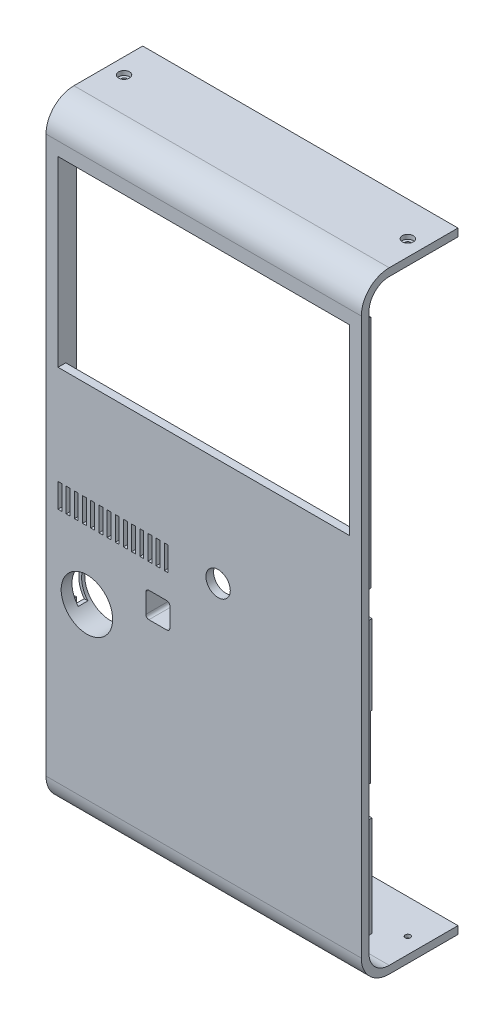
SolidWorks part; units mm, degrees
ref_plane "Alzado" through (0, 0, 0) normal (0, 0, 1) x (1, 0, 0)
ref_plane "Planta" through (0, 0, 0) normal (0, 1, 0) x (1, 0, 0)
ref_plane "Vista lateral" through (0, 0, 0) normal (1, 0, 0) x (0, 0, -1)
sketch "Croquis2" plane through (0, 0, 0) normal (1, 0, 0) x (0, 0, -1)
  line L0 (37, 0) -> (37, -3.2)
  line L1 (8.4, 0) -> (37, 0)
  line L2 (0, 8.4) -> (0, 239.6)
  line L3 (8.4, 248) -> (37, 248)
  line L5 (37, 248) -> (37, 251.2)
  line L6 (37, -3.2) -> (8.4, -3.2)
  line L7 (37, 251.2) -> (8.4, 251.2)
  line L8 (-3.2, 239.6) -> (-3.2, 8.4)
  arc A0 (8.4, 248) -> (0, 239.6) centre (8.4, 239.6) ccw
  arc A1 (0, 8.4) -> (8.4, 0) centre (8.4, 8.4) ccw
  arc A4 (8.4, 251.2) -> (-3.2, 239.6) centre (8.4, 239.6) ccw
  arc A5 (-3.2, 8.4) -> (8.4, -3.2) centre (8.4, 8.4) ccw
  point P9 (0, 0)
  dimension "D3" = 8.4
  dimension "D6" = 3.2
  dimension "D5" = 11.6
  dimension "D1" = 248
  dimension "D2" = 37
  dimension "D4" = 3.2
extrude "Saliente-Extruir1" add sketch "Croquis2" along normal blind 131.1
sketch "Croquis3" plane through (0, 251.2, 0) normal (0, 1, 0) x (1, 0, 0)
  line L0 (131.1, 37) -> (0, 37) construction
  line L1 (0, 37) -> (0, 8.4) construction
  line L2 (65.55, 37) -> (65.55, 8.4) construction
  line L4 (131.1, 8.4) -> (0, 8.4) construction
  circle A0 centre (6.55, 22.7) radius 1.1
  circle A1 centre (124.55, 22.7) radius 1.1
  dimension "D3" = 2.2
  dimension "D1" = 14.3
  dimension "D2" = 6.55
extrude "Cortar-Extruir1" cut sketch "Croquis3" against normal through all
sketch "Croquis4" plane through (0, 0, 3.2) normal (0, 0, 1) x (1, 0, 0)
  line L0 (131.1, 8.4) -> (0, 8.4) construction
  line L1 (0, 249.9) -> (0, 248) construction
  line L2 (65.55, 239.6) -> (65.55, 8.4) construction
  line L4 (5, 234) -> (126.1, 234)
  line L5 (126.1, 234) -> (126.1, 158.2)
  line L6 (126.1, 158.2) -> (5, 158.2)
  line L7 (5, 158.2) -> (5, 234)
  line L8 (0, 239.6) -> (0, 8.4) construction
  line L9 (131.1, 239.6) -> (0, 239.6) construction
  line L10 (8.4, 117) -> (8.4, 107)
  line L11 (41.5, 86.1) -> (51.5, 86.1)
  line L12 (41.5, 86.1) -> (41.5, 96.7)
  line L13 (41.5, 96.7) -> (51.5, 96.7)
  line L14 (51.5, 86.1) -> (51.5, 96.7)
  line L15 (5, 117) -> (6.6, 117)
  line L16 (5, 117) -> (5, 107)
  line L17 (5, 107) -> (6.6, 107)
  line L18 (6.6, 117) -> (6.6, 107)
  line L19 (8.4, 117) -> (10, 117)
  line L20 (10, 117) -> (10, 107)
  line L21 (8.4, 107) -> (10, 107)
  line L22 (11.8, 117) -> (11.8, 107)
  line L23 (11.8, 117) -> (13.4, 117)
  line L24 (13.4, 117) -> (13.4, 107)
  line L25 (11.8, 107) -> (13.4, 107)
  line L26 (15.2, 117) -> (15.2, 107)
  line L27 (15.2, 117) -> (16.8, 117)
  line L28 (16.8, 117) -> (16.8, 107)
  line L29 (15.2, 107) -> (16.8, 107)
  line L30 (18.6, 117) -> (18.6, 107)
  line L31 (18.6, 117) -> (20.2, 117)
  line L32 (20.2, 117) -> (20.2, 107)
  line L33 (18.6, 107) -> (20.2, 107)
  line L34 (22, 117) -> (22, 107)
  line L35 (22, 117) -> (23.6, 117)
  line L36 (23.6, 117) -> (23.6, 107)
  line L37 (22, 107) -> (23.6, 107)
  line L38 (25.4, 117) -> (25.4, 107)
  line L39 (25.4, 117) -> (27, 117)
  line L40 (27, 117) -> (27, 107)
  line L41 (25.4, 107) -> (27, 107)
  line L42 (28.8, 117) -> (28.8, 107)
  line L43 (28.8, 117) -> (30.4, 117)
  line L44 (30.4, 117) -> (30.4, 107)
  line L45 (28.8, 107) -> (30.4, 107)
  line L46 (32.2, 117) -> (32.2, 107)
  line L47 (32.2, 117) -> (33.8, 117)
  line L48 (33.8, 117) -> (33.8, 107)
  line L49 (32.2, 107) -> (33.8, 107)
  line L50 (35.6, 117) -> (35.6, 107)
  line L51 (35.6, 117) -> (37.2, 117)
  line L52 (37.2, 117) -> (37.2, 107)
  line L53 (35.6, 107) -> (37.2, 107)
  line L54 (39, 117) -> (39, 107)
  line L55 (39, 117) -> (40.6, 117)
  line L56 (40.6, 117) -> (40.6, 107)
  line L57 (39, 107) -> (40.6, 107)
  line L58 (42.4, 117) -> (42.4, 107)
  line L59 (42.4, 117) -> (44, 117)
  line L60 (44, 117) -> (44, 107)
  line L61 (42.4, 107) -> (44, 107)
  line L62 (45.8, 117) -> (45.8, 107)
  line L63 (45.8, 117) -> (47.4, 117)
  line L64 (47.4, 117) -> (47.4, 107)
  line L65 (45.8, 107) -> (47.4, 107)
  line L66 (49.2, 117) -> (49.2, 107)
  line L67 (49.2, 117) -> (50.8, 117)
  line L68 (50.8, 117) -> (50.8, 107)
  line L69 (49.2, 107) -> (50.8, 107)
  circle A0 centre (17, 78.7) radius 10.7
  circle A1 centre (71.55, 113.5) radius 5.07
  point P0 (5, 234)
  point P1 (66.5275, 113.5)
  point P9 (126.1, 234)
  dimension "D6" = 21.4
  dimension "D16" = 10.14
  dimension "D2" = 121.1
  dimension "D3" = 75.8
  dimension "D4" = 17
  dimension "D5" = 169.3
  dimension "D7" = 24.5
  dimension "D8" = 151.3
  dimension "D9" = 10
  dimension "D10" = 10.6
  dimension "D11" = 131
  dimension "D12" = 10
  dimension "D13" = 1.6
  dimension "D14" = 5
  dimension "D17" = 134.5
  dimension "D18" = 14
  dimension "D19" = 6
  dimension "D15" = 14
extrude "Cortar-Extruir2" cut sketch "Croquis4" against normal through all
sketch "Croquis7" plane through (0, 0, 0) normal (0, 0, -1) x (-1, 0, 0)
  line L5 (-127.46, 125.3) -> (-127.96, 125.3)
  line L10 (-126.1, 234) -> (-127.46, 234)
  line L11 (-126.1, 234) -> (-126.1, 136)
  line L12 (-126.1, 136) -> (-127.46, 136)
  line L13 (-127.46, 234) -> (-127.46, 136)
  line L14 (-5, 234) -> (-3.64, 234)
  line L15 (-5, 234) -> (-5, 136)
  line L16 (-5, 136) -> (-3.64, 136)
  line L17 (-3.64, 234) -> (-3.64, 136)
  line L18 (-127.46, 125.3) -> (-126.1, 125.3)
  line L20 (-127.46, 66.3) -> (-126.1, 66.3)
  line L21 (-126.1, 125.3) -> (-126.1, 66.3)
  line L22 (-3.64, 125.3) -> (-5, 125.3)
  line L24 (-3.64, 66.3) -> (-5, 66.3)
  line L25 (-5, 125.3) -> (-5, 66.3)
  line L27 (-127.46, 66.3) -> (-127.96, 66.3)
  line L28 (-127.96, 125.3) -> (-127.96, 66.3)
  line L29 (-3.64, 125.3) -> (-3.14, 125.3)
  line L31 (-3.64, 66.3) -> (-3.14, 66.3)
  line L32 (-3.14, 125.3) -> (-3.14, 66.3)
  line L33 (-126.1, 53.5) -> (-127.96, 53.5)
  line L34 (-126.1, 53.5) -> (-126.1, 11.9)
  line L35 (-126.1, 11.9) -> (-127.96, 11.9)
  line L36 (-127.96, 53.5) -> (-127.96, 11.9)
  line L37 (-5, 53.5) -> (-3.14, 53.5)
  line L38 (-5, 53.5) -> (-5, 11.9)
  line L39 (-5, 11.9) -> (-3.14, 11.9)
  line L40 (-3.14, 53.5) -> (-3.14, 11.9)
  dimension "D1" = 1.36
  dimension "D2" = 98
  dimension "D3" = 10.7
  dimension "D4" = 59
  dimension "D5" = 0.5
  dimension "D6" = 0.5
  dimension "D7" = 12.8
  dimension "D8" = 1.36
  dimension "D9" = 1.36
  dimension "D10" = 0.5
  dimension "D11" = 1.36
  dimension "D12" = 41.6
extrude "Saliente-Extruir2" add sketch "Croquis7" along normal blind 4.4
sketch "Croquis8" plane through (0, 251.2, 0) normal (0, 1, 0) x (1, 0, 0)
  circle A0 centre (6.55, 22.7) radius 2.27
  circle A1 centre (124.55, 22.7) radius 2.27
  dimension "D1" = 4.54
extrude "Cortar-Extruir3" cut sketch "Croquis8" against normal blind 1.8
sketch "Croquis9" plane through (0, -3.2, 0) normal (0, -1, 0) x (1, 0, 0)
  circle A0 centre (124.55, -22.7) radius 2.27
  circle A1 centre (6.55, -22.7) radius 2.27
  dimension "D1" = 4.54
extrude "Cortar-Extruir4" cut sketch "Croquis9" against normal blind 1.8
sketch "Croquis10" plane through (0, 0, 0) normal (0, 0, -1) x (-1, 0, 0)
  line L0 (-41.5, 86.1) -> (-51.5, 86.1) construction
  line L1 (-51.5, 96.7) -> (-41.5, 96.7)
  line L2 (-51.5, 96.7) -> (-51.5, 86.1)
  line L3 (-51.5, 86.1) -> (-41.5, 86.1)
  line L4 (-41.5, 96.7) -> (-41.5, 86.1)
  line L5 (-52.7, 97.9) -> (-40.3, 97.9)
  line L6 (-40.3, 97.9) -> (-40.3, 84.9)
  line L7 (-40.3, 84.9) -> (-52.7, 84.9)
  line L8 (-52.7, 84.9) -> (-52.7, 97.9)
  line L9 (-41.5, 96.7) -> (-41.5, 86.1) construction
  circle A0 centre (-17, 78.7) radius 11.9
  circle A1 centre (-17, 78.7) radius 10.7 construction
  circle A2 centre (-17, 78.7) radius 10.7
  dimension "D1" = 1.2
  dimension "D2" = 1.2
  dimension "D3" = 1.2
  dimension "D4" = 1.2
  dimension "D5" = 1.2
extrude "Saliente-Extruir4" add sketch "Croquis10" along normal blind 6.6
fillet "Redondeo2" radius 1.28 4 edges at (51.5, 86.1, -1.7) (51.5, 96.7, -1.7) (41.5, 96.7, -1.7) (41.5, 86.1, -1.7)
ref_plane "Plano1" through (-10, 0, 0) normal (-1, 0, 0) x (0, 0, 1)
sketch "Croquis11" plane through (-10, 0, 0) normal (-1, 0, 0) x (0, 0, 1)
  line L0 (-6.6, 78.7) -> (0, 78.7) construction
  line L1 (-6.6, 90.6) -> (-6.6, 66.8) construction
  line L4 (-5.3, 71.7) -> (-1.3, 71.7)
  line L5 (-5.3, 71.7) -> (-5.3, 85.7)
  line L6 (-5.3, 85.7) -> (-1.3, 85.7)
  line L7 (-1.3, 71.7) -> (-1.3, 85.7)
  line L8 (-5.3, 71.7) -> (-1.3, 85.7) construction
  line L9 (-5.3, 85.7) -> (-1.3, 71.7) construction
  line L10 (0, 8.4) -> (0, 239.6) construction
  point P6 (-3.3, 78.7)
  dimension "D1" = 4
  dimension "D2" = 14
extrude "Cortar-Extruir5" cut sketch "Croquis11" against normal up to surface (18.9074 mm away)
sketch "Croquis13" plane through (0, 0, -6.6) normal (0, 0, -1) x (-1, 0, 0)
  line L0 (-50.22, 96.7) -> (-42.78, 96.7)
  line L1 (-50.22, 86.1) -> (-42.78, 86.1)
  line L2 (-41.5, 87.38) -> (-41.5, 95.42)
  line L3 (-51.5, 87.38) -> (-51.5, 95.42)
  line L4 (-52.7, 97.9) -> (-52.7, 84.9)
  line L5 (-52.7, 84.9) -> (-40.3, 84.9)
  line L6 (-40.3, 84.9) -> (-40.3, 97.9)
  line L7 (-40.3, 97.9) -> (-52.7, 97.9)
  line L8 (-52.7, 97.9) -> (-52.7, 84.9)
  line L9 (-52.7, 84.9) -> (-40.3, 84.9)
  line L10 (-40.3, 84.9) -> (-40.3, 97.9)
  line L11 (-40.3, 97.9) -> (-52.7, 97.9)
  circle A0 centre (-50.22, 95.42) radius 1.28
  circle A1 centre (-50.22, 87.38) radius 1.28
  circle A2 centre (-42.78, 87.38) radius 1.28
  circle A3 centre (-42.78, 95.42) radius 1.28
  line M5 (-52.7, 97.9) -> (-52.7, 84.9)
  line M6 (-52.7, 84.9) -> (-40.3, 84.9)
  line M7 (-40.3, 84.9) -> (-40.3, 97.9)
  line M8 (-40.3, 97.9) -> (-52.7, 97.9)
  line M9 (-51.5, 87.38) -> (-51.5, 95.42)
  arc M10 (-51.5, 95.42) -> (-50.22, 96.7) centre (-50.22, 95.42) cw
  line M11 (-50.22, 96.7) -> (-42.78, 96.7)
  arc M12 (-42.78, 96.7) -> (-41.5, 95.42) centre (-42.78, 95.42) cw
  line M13 (-41.5, 95.42) -> (-41.5, 87.38)
  arc M14 (-41.5, 87.38) -> (-42.78, 86.1) centre (-42.78, 87.38) cw
  line M15 (-42.78, 86.1) -> (-50.22, 86.1)
  arc M16 (-50.22, 86.1) -> (-51.5, 87.38) centre (-50.22, 87.38) cw
  dimension "D1" = 0
extrude "Saliente-Extruir6" add sketch "Croquis13" along normal blind 1 contours M8 M5 M6 M7 M16 M9 M10 M11 M12 M13 M14 M15
sketch "Croquis14" plane through (0, 0, 0) normal (0, 0, -1) x (-1, 0, 0)
  line L0 (-71.55, 113.5) -> (-71.55, 74.9205) construction
  circle A0 centre (-71.55, 88.8) radius 1.5
  circle A1 centre (-71.55, 88.8) radius 3.2
  dimension "D2" = 3
  dimension "D3" = 6.4
  dimension "D1" = 24.7
extrude "Saliente-Extruir7" add sketch "Croquis14" along normal blind 8.4
fillet "Redondeo3" radius 3.84 1 edges at (74.75, 88.8, 0)
sketch "Croquis17" plane through (127.46, 0, 0) normal (1, 0, 0) x (0, 0, -1)
  line L0 (4.4, 234) -> (4.4, 136) construction
  line L1 (0, 234) -> (4.4, 234)
  line L2 (0, 234) -> (0, 233.6)
  line L3 (0, 233.6) -> (4.4, 233.6)
  line L4 (4.4, 234) -> (4.4, 233.6)
  dimension "D1" = 0.4
extrude "Cortar-Extruir6" cut sketch "Croquis17" against normal through all
fillet "Redondeo4" radius 1.6 2 edges at (52.7, 91.4, 0) (40.3, 91.4, 0)
sketch "Croquis19" plane through (0, 0, 0) normal (0, 0, -1) x (-1, 0, 0)
  line L5 (-17, 66.8) -> (-17, 78.7) construction
  line L18 (-17, 78.7) -> (-17, 90.6) construction
  circle A2 centre (-17, 78.7) radius 11.9 construction
  circle A3 centre (-17, 90.6) radius 1.12
  circle A4 centre (-17, 66.8) radius 1.12
  dimension "D1" = 2.24
extrude "Saliente-Extruir8" add sketch "Croquis19" along normal up to surface (6.6 mm away) up to face at (5.1, 78.7, -6.6)
fillet "Redondeo5" radius 1 1 edges at (28.9, 78.7, 0)
sketch "Croquis21" plane through (127.96, 0, 0) normal (1, 0, 0) x (0, 0, -1)
  line L1 (4.4, 66.3) -> (3.8, 66.3)
  line L2 (4.4, 66.3) -> (4.4, 92.3)
  line L3 (4.4, 92.3) -> (3.8, 92.3)
  line L4 (3.8, 66.3) -> (3.8, 92.3)
  dimension "D1" = 0.6
  dimension "D2" = 26
extrude "Cortar-Extruir8" cut sketch "Croquis21" against normal up to vertex
sketch "Croquis23" plane through (0, 0, 3.2) normal (0, 0, 1) x (1, 0, 0)
  line L0 (126.1, 158.2) -> (126.1, 234) construction
  line L1 (5, 158.2) -> (126.1, 158.2)
  line L2 (5, 158.2) -> (5, 158.1)
  line L3 (5, 158.1) -> (126.1, 158.1)
  line L4 (126.1, 158.2) -> (126.1, 158.1)
  dimension "D1" = 0.1
extrude "Cortar-Extruir9" cut sketch "Croquis23" against normal through all
